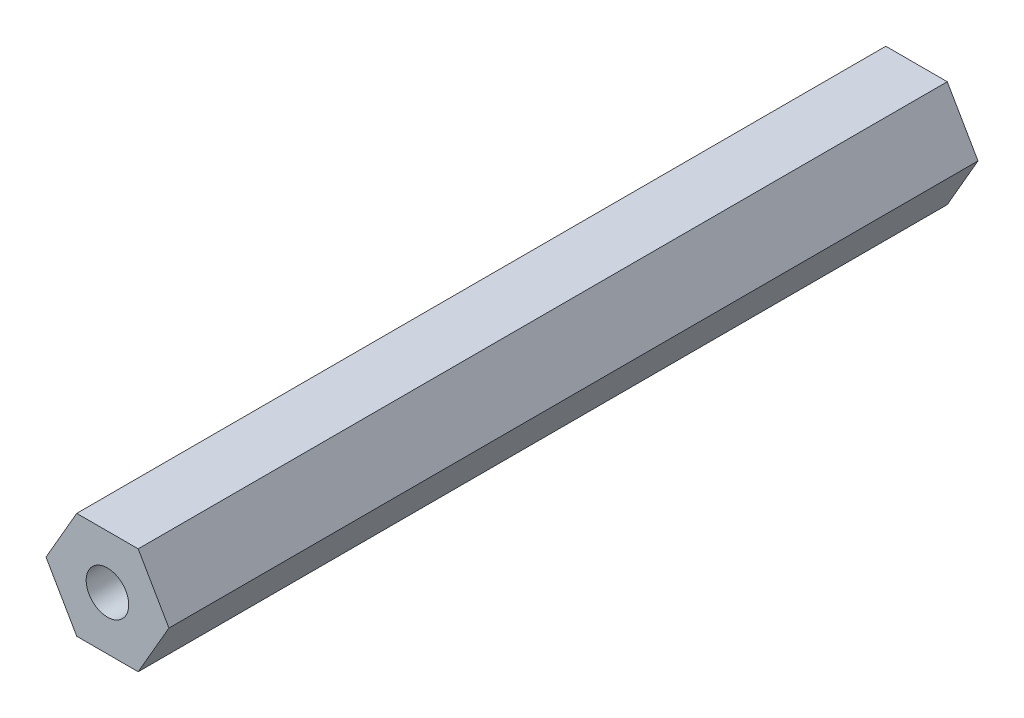
SolidWorks part; units mm, degrees
material "Copper"
ref_plane "Front Plane" through (0, 0, 0) normal (0, 0, 1) x (1, 0, 0)
ref_plane "Top Plane" through (0, 0, 0) normal (0, 1, 0) x (1, 0, 0)
ref_plane "Right Plane" through (0, 0, 0) normal (1, 0, 0) x (0, 0, -1)
sketch "Sketch1" plane through (0, 0, 0) normal (0, 0, 1) x (1, 0, 0)
  line L0 (0, 0) -> (2.8868, 0) construction
  line L1 (2.8868, 0) -> (1.4434, 2.5)
  line L2 (1.4434, 2.5) -> (-1.4434, 2.5)
  line L3 (-1.4434, 2.5) -> (-2.8868, 0)
  line L4 (-2.8868, 0) -> (-1.4434, -2.5)
  line L5 (-1.4434, -2.5) -> (1.4434, -2.5)
  line L6 (1.4434, -2.5) -> (2.8868, 0)
  circle A0 centre (0, 0) radius 2.5 construction
  dimension "D1" = 5
extrude "Boss-Extrude1" add sketch "Sketch1" along normal blind 38
sketch "Sketch2" plane through (0, 0, 38) normal (0, 0, 1) x (1, 0, 0)
  circle A0 centre (0, 0) radius 1
  dimension "D1" = 2
extrude "Cut-Extrude1" cut sketch "Sketch2" against normal through all
